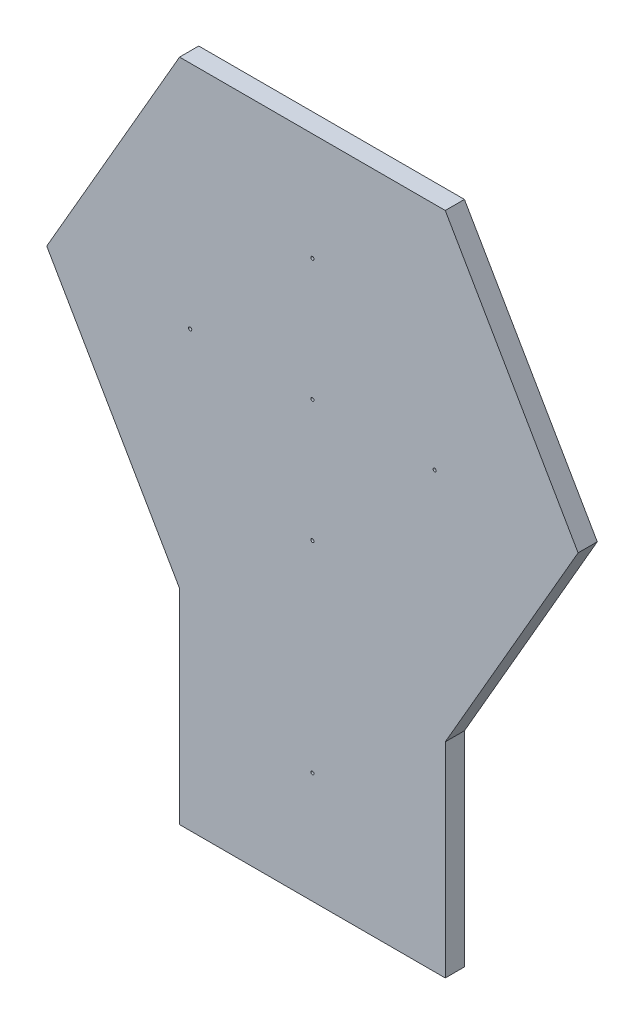
SolidWorks part; units mm, degrees
ref_plane "Front Plane" through (0, 0, 0) normal (0, 0, 1) x (1, 0, 0)
ref_plane "Top Plane" through (0, 0, 0) normal (0, 1, 0) x (1, 0, 0)
ref_plane "Right Plane" through (0, 0, 0) normal (1, 0, 0) x (0, 0, -1)
sketch "Sketch1" plane through (0, 0, 0) normal (0, 0, 1) x (1, 0, 0)
  line L0 (0, 0) -> (-131.9823, 228.6)
  line L1 (-131.9823, 228.6) -> (131.9823, 228.6)
  line L2 (131.9823, 228.6) -> (0, 0)
  line L3 (0, 0) -> (131.9823, 228.6)
  line L4 (131.9823, 228.6) -> (263.9645, 0)
  line L5 (263.9645, 0) -> (0, 0)
  line L6 (0, 0) -> (263.9645, 0)
  line L7 (263.9645, 0) -> (131.9823, -228.6)
  line L8 (131.9823, -228.6) -> (0, 0)
  line L9 (0, 0) -> (131.9823, -228.6)
  line L10 (131.9823, -228.6) -> (-131.9823, -228.6)
  line L11 (-131.9823, -228.6) -> (0, 0)
  line L12 (0, 0) -> (-131.9823, -228.6)
  line L13 (-131.9823, -228.6) -> (-263.9645, 0)
  line L14 (-263.9645, 0) -> (0, 0)
  line L15 (0, 0) -> (-263.9645, 0)
  line L16 (-263.9645, 0) -> (-131.9823, 228.6)
  line L17 (-131.9823, 228.6) -> (0, 0)
  point P29 (0, 0)
  dimension "D1" = 60
  dimension "D3" = 228.6
  dimension "D5" = 6
extrude "Boss-Extrude1" add sketch "Sketch1" along normal blind 19.05
sketch "Sketch2" plane through (0, 0, 19.05) normal (0, 0, 1) x (1, 0, 0)
  line L1 (-131.9823, -228.6) -> (131.9823, -228.6)
  line L2 (-131.9823, -228.6) -> (-131.9823, -431.8)
  line L3 (-131.9823, -431.8) -> (131.9823, -431.8)
  line L4 (131.9823, -228.6) -> (131.9823, -431.8)
  dimension "D1" = 0
  dimension "D2" = 203.2
extrude "Boss-Extrude2" add sketch "Sketch2" against normal blind 19.05
sketch "Sketch4" plane through (0, 0, 19.05) normal (0, 0, 1) x (1, 0, 0)
  circle A0 centre (0, 0) radius 1.5875
  circle A1 centre (0, -321.31) radius 1.5875
  dimension "D1" = 321.31
  dimension "D2" = 3.175
  dimension "D3" = 3.175
extrude "Cut-Extrude1" cut sketch "Sketch4" against normal through all
sketch "Sketch5" plane through (0, 0, 19.05) normal (0, 0, 1) x (1, 0, 0)
  circle A0 centre (-121.4438, 0) radius 1.5875
  circle A1 centre (0, 0) radius 1.5875 construction
  circle A2 centre (0, 121.4437) radius 1.5875
  circle A3 centre (121.4438, 0) radius 1.5875
  circle A4 centre (0, -121.4438) radius 1.5875
  point P13 (0, 0)
  dimension "D1" = 3.175
  dimension "D2" = 121.4438
  dimension "D3" = 4
extrude "Cut-Extrude2" cut sketch "Sketch5" against normal through all
